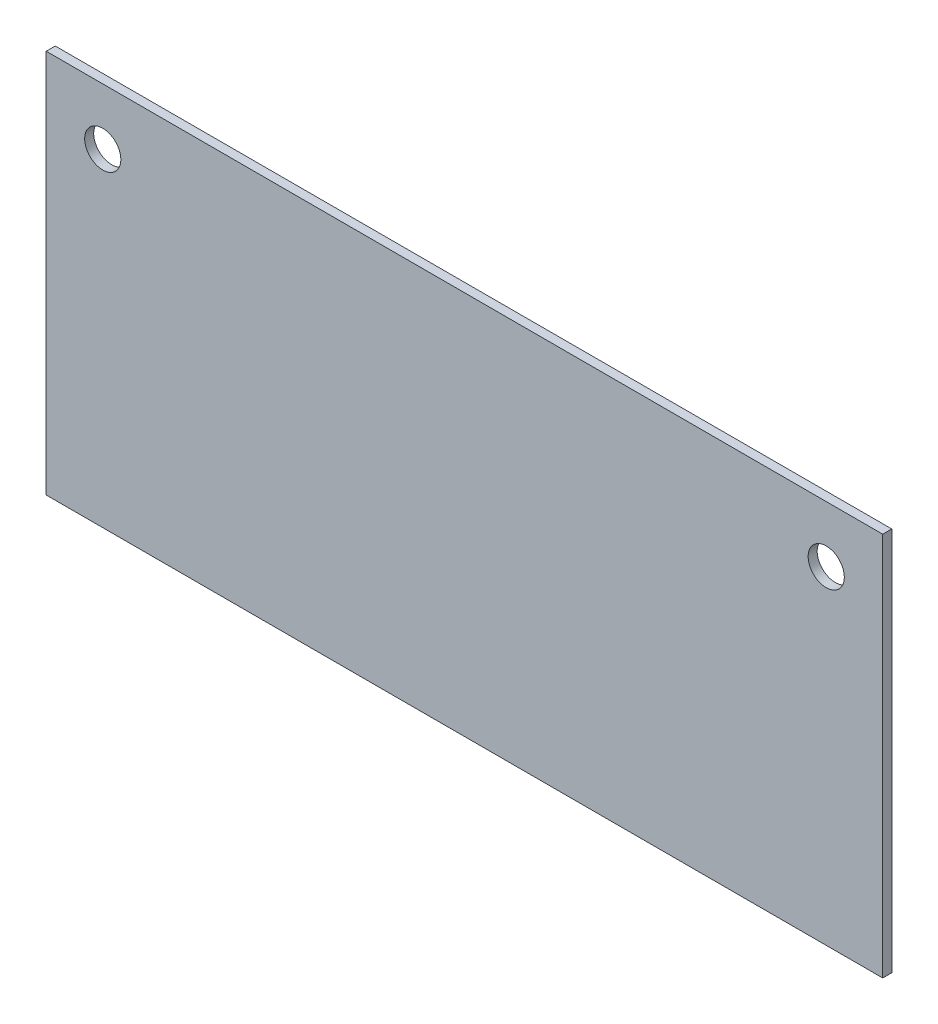
SolidWorks part; units mm, degrees
material "Cast Alloy Steel"
ref_plane "Front Plane" through (0, 0, 0) normal (0, 0, 1) x (1, 0, 0)
ref_plane "Top Plane" through (0, 0, 0) normal (0, 1, 0) x (1, 0, 0)
ref_plane "Right Plane" through (0, 0, 0) normal (1, 0, 0) x (0, 0, -1)
sketch "Sketch1" plane through (0, 0, 0) normal (0, 0, 1) x (1, 0, 0)
  line L1 (-44.702, 41.4382) -> (29.298, 41.4382)
  line L2 (-44.702, 41.4382) -> (-44.702, 7.4382)
  line L3 (-44.702, 7.4382) -> (29.298, 7.4382)
  line L4 (29.298, 41.4382) -> (29.298, 7.4382)
  circle A0 centre (-39.702, 36.4382) radius 1.6
  circle A1 centre (24.298, 36.4382) radius 1.6
  dimension "D3" = 3.2
  dimension "D4" = 5
  dimension "D1" = 74
  dimension "D2" = 34
  dimension "D5" = 5
  dimension "D6" = 2
extrude "Boss-Extrude1" add sketch "Sketch1" along normal blind 0.8
